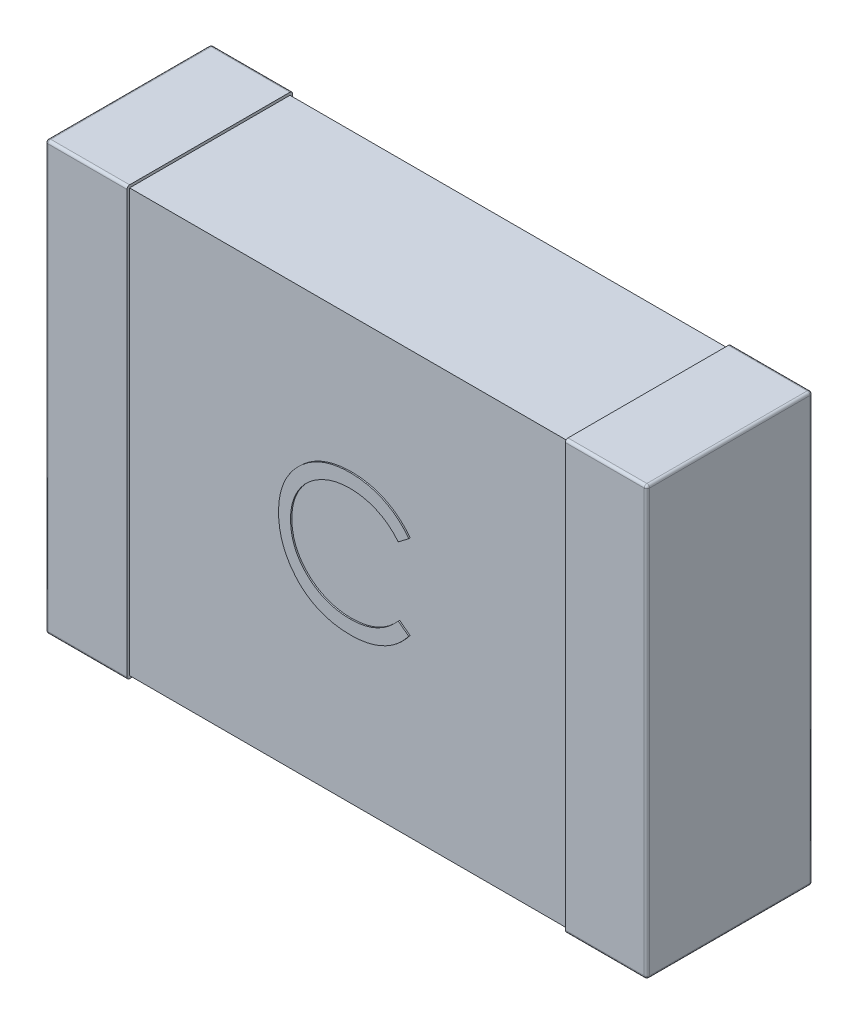
SolidWorks part; units mm, degrees
ref_plane "前视基准面" through (0, 0, 0) normal (0, 0, 1) x (1, 0, 0)
ref_plane "上视基准面" through (0, 0, 0) normal (0, 1, 0) x (1, 0, 0)
ref_plane "右视基准面" through (0, 0, 0) normal (1, 0, 0) x (0, 0, -1)
sketch "草图3" plane through (0, 0, 0) normal (0, 0, 1) x (1, 0, 0)
  line L0 (0, 1.8533) -> (0, -1.7461) construction
  line L1 (-2.25, 1.6) -> (-1.64, 1.6)
  line L2 (-2.25, 1.6) -> (-2.25, -1.6)
  line L3 (-2.25, -1.6) -> (-1.64, -1.6)
  line L4 (-1.64, 1.6) -> (-1.64, -1.6)
  line L5 (-2.25, 1.6) -> (-1.64, -1.6) construction
  line L6 (-2.25, -1.6) -> (-1.64, 1.6) construction
  line L7 (2.25, -1.6) -> (1.64, 1.6) construction
  line L8 (2.25, 1.6) -> (1.64, -1.6) construction
  line L9 (1.64, 1.6) -> (1.64, -1.6)
  line L10 (2.25, -1.6) -> (1.64, -1.6)
  line L11 (2.25, 1.6) -> (2.25, -1.6)
  line L12 (2.25, 1.6) -> (1.64, 1.6)
  point P0 (-1.945, 0)
  point P12 (1.945, 0)
  dimension "D1" = 0.61
  dimension "D2" = 3.2
  dimension "D3" = 2.25
extrude "凸台-拉伸1" add sketch "草图3" along normal blind 1.22 and the other way blind 0.02
sketch "草图5" plane through (0, 0, 0) normal (1, 0, 0) x (0, 0, -1)
  line L0 (0, 1.58) -> (0, -1.58)
  line L1 (0, -1.58) -> (-1.2, -1.58)
  line L2 (-1.2, -1.58) -> (-1.2, 1.58)
  line L3 (-1.2, 1.58) -> (0, 1.58)
  dimension "D1" = 3.16
  dimension "D2" = 1.2
extrude "凸台-拉伸3" add sketch "草图5" along normal mid plane 3.32
fillet "圆角3" radius 0.02 16 edges at (2.25, 0, -0.02) (2.25, -1.6, 0.6) (2.25, 0, 1.22) (2.25, 1.6, 0.6) (-2.25, 0, -0.02) (-2.25, 1.6, 0.6) (-2.25, 0, 1.22) (-2.25, -1.6, 0.6) (1.945, 1.6, -0.02) (1.945, -1.6, -0.02) (1.945, -1.6, 1.22) (1.945, 1.6, 1.22) (-1.945, -1.6, -0.02) (-1.945, -1.6, 1.22) (-1.945, 1.6, -0.02) (-1.945, 1.6, 1.22)
sketch "草图6" plane through (0, 0, 1.2) normal (0, 0, 1) x (1, 0, 0)
  text T0 "C" font "Century Gothic" height 1
extrude "凸台-拉伸4" add sketch "草图6" along normal blind 0.01
